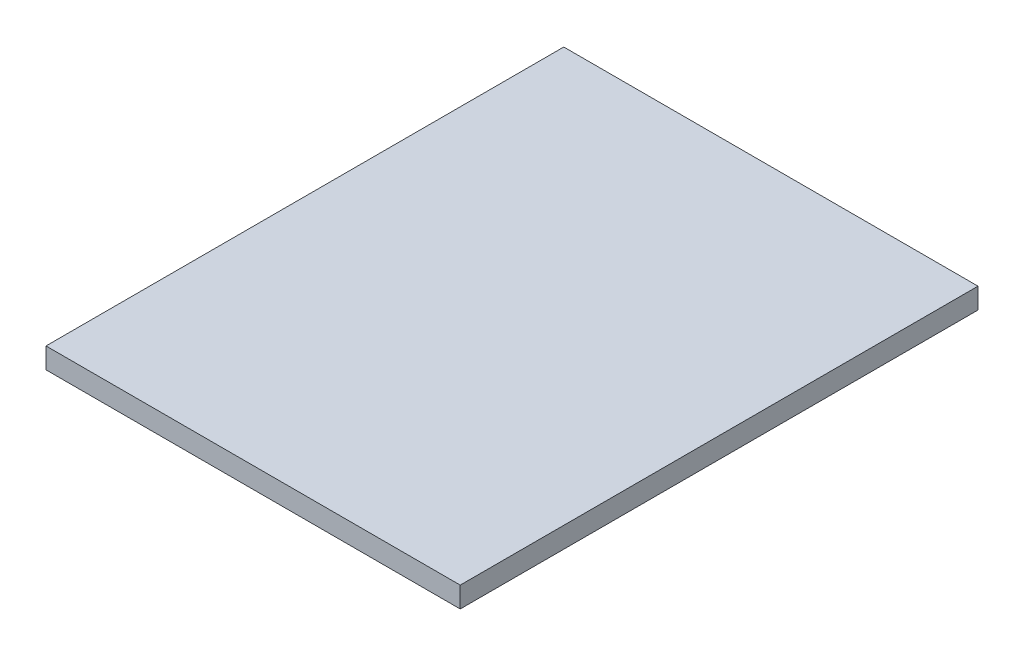
SolidWorks part; units mm, degrees
ref_plane "Спереди" through (0, 0, 0) normal (0, 0, 1) x (1, 0, 0)
ref_plane "Сверху" through (0, 0, 0) normal (0, 1, 0) x (1, 0, 0)
ref_plane "Справа" through (0, 0, 0) normal (1, 0, 0) x (0, 0, -1)
sketch "Эскиз1" plane through (0, 0, 0) normal (0, 0, 1) x (1, 0, 0)
  line L1 (-100, 5) -> (100, 5)
  line L2 (-100, 5) -> (-100, -5)
  line L3 (-100, -5) -> (100, -5)
  line L4 (100, 5) -> (100, -5)
  point P4 (-100, 0)
  point P6 (0, 5)
  dimension "D1" = 10
  dimension "D2" = 200
extrude "Бобышка-Вытянуть1" add sketch "Эскиз1" along normal blind 250
ref_plane "Плоскость1" through (0, 0, 0) normal (1, 0, 0) x (0, 0, -1)
